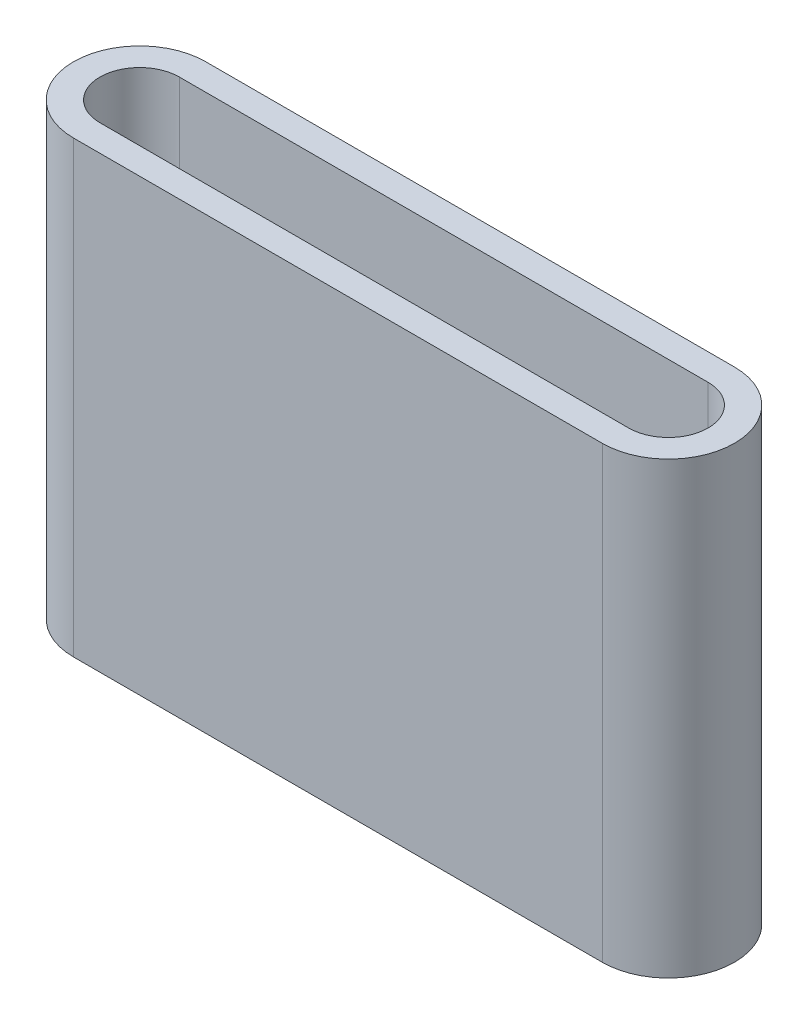
SolidWorks part; units mm, degrees
ref_plane "前视基准面" through (0, 0, 0) normal (0, 0, 1) x (1, 0, 0)
ref_plane "上视基准面" through (0, 0, 0) normal (0, 1, 0) x (1, 0, 0)
ref_plane "右视基准面" through (0, 0, 0) normal (1, 0, 0) x (0, 0, -1)
other "Configuration Table"
sketch "草图1" plane through (0, 0, 0) normal (0, 1, 0) x (1, 0, 0)
  line L0 (0, 0) -> (100, 0) construction
  line L1 (0, 12.5) -> (100, 12.5)
  line L2 (0, -12.5) -> (100, -12.5)
  arc A0 (0, 12.5) -> (0, -12.5) centre (0, 0) ccw
  arc A1 (100, -12.5) -> (100, 12.5) centre (100, 0) ccw
  point P2 (50, 0)
  dimension "D1" = 100
  dimension "D2" = 25
extrude "凸台-拉伸1" add sketch "草图1" along normal blind 20 and the other way blind 10
sketch "草图2" plane through (0, 20, 0) normal (0, 1, 0) x (1, 0, 0)
  line L2 (0, -12.5) -> (100, -12.5)
  line L3 (100, 12.5) -> (0, 12.5)
  line L4 (0, -12.5) -> (100, -12.5)
  line L5 (100, 12.5) -> (0, 12.5)
  arc A2 (0, 12.5) -> (0, -12.5) centre (0, 0) ccw
  arc A3 (100, -12.5) -> (100, 12.5) centre (100, 0) ccw
  arc A4 (0, 12.5) -> (0, -12.5) centre (0, 0) ccw
  arc A5 (100, -12.5) -> (100, 12.5) centre (100, 0) ccw
  dimension "D1" = 0
extrude "拉伸-薄壁1" add sketch "草图2" along normal blind 55 thin thin type one direction reverse wall 5
